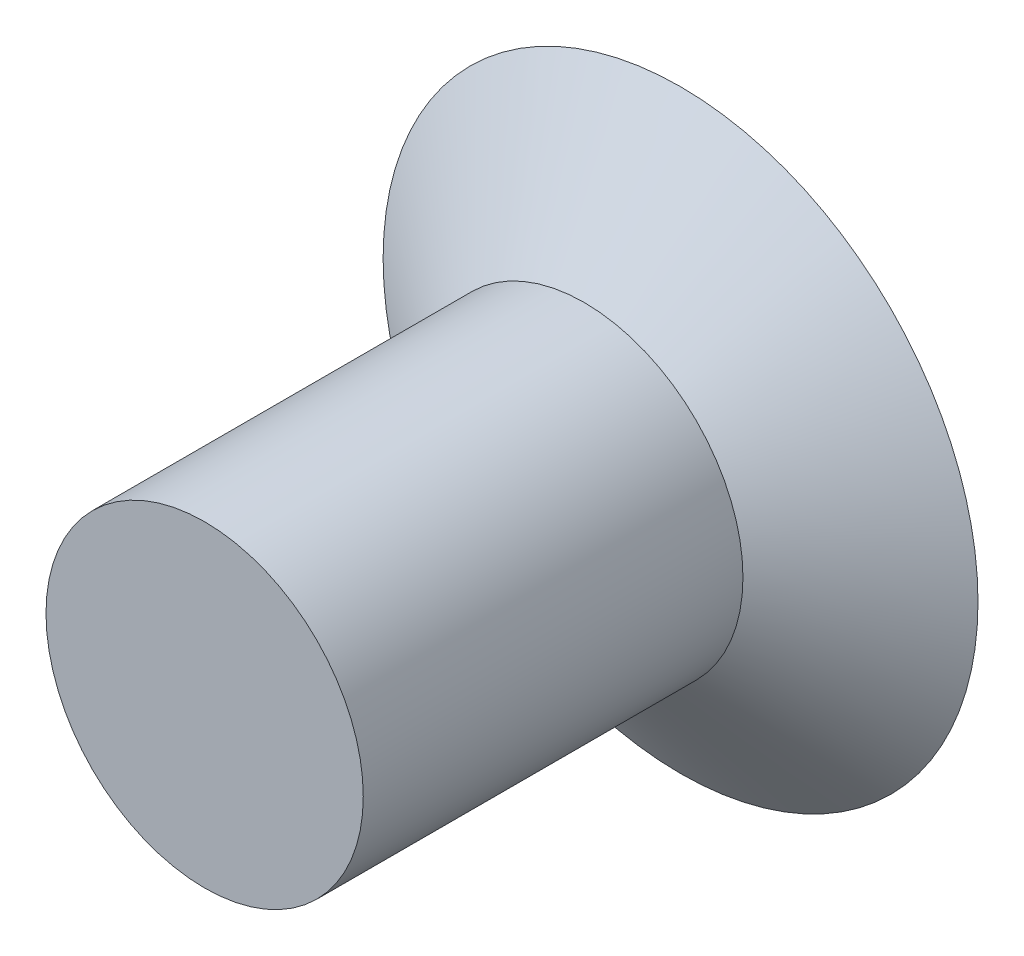
SolidWorks part; units mm, degrees
ref_plane "前视基准面" through (0, 0, 0) normal (0, 0, 1) x (1, 0, 0)
ref_plane "上视基准面" through (0, 0, 0) normal (0, 1, 0) x (1, 0, 0)
ref_plane "右视基准面" through (0, 0, 0) normal (1, 0, 0) x (0, 0, -1)
sketch "草图1" plane through (0, 0, 0) normal (0, 0, 1) x (1, 0, 0)
  circle A0 centre (0, 0) radius 2
  dimension "D1" = 4
extrude "凸台-拉伸1" add sketch "草图1" along normal blind 6
sketch "草图2" plane through (0, 0, 0) normal (0, 1, 0) x (1, 0, 0)
  line L0 (0, 0) -> (3.75, 0)
  line L1 (3.75, 0) -> (0, -2.6)
  line L2 (0, -2.6) -> (0, 0)
  dimension "D1" = 2.6
  dimension "D2" = 3.75
revolve "旋转1" add sketch "草图2" angle 360 about L2
